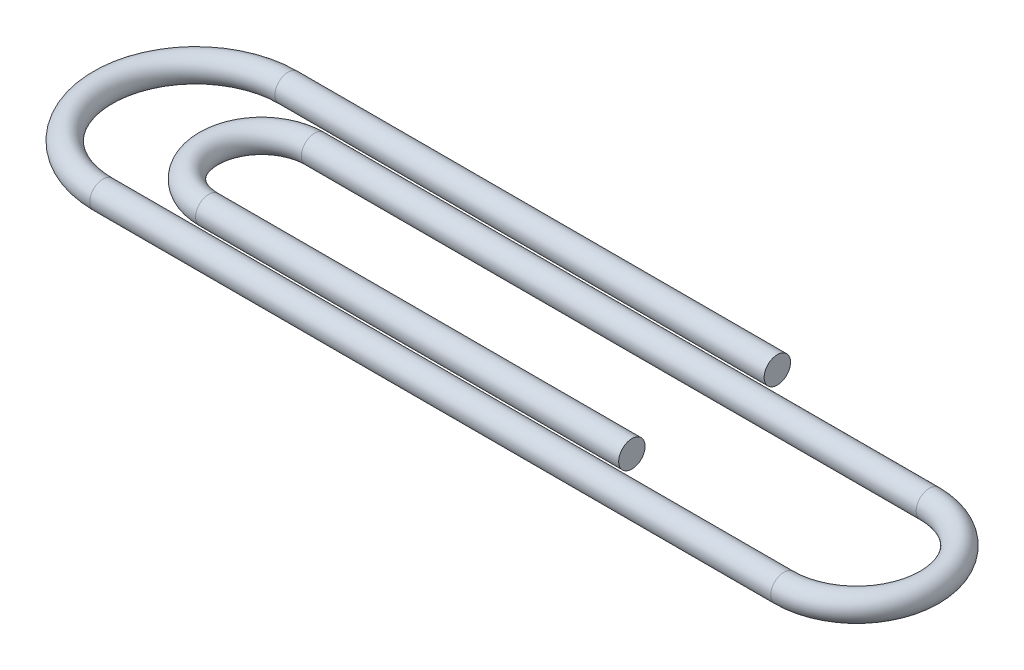
SolidWorks part; units mm, degrees
ref_plane "Front Plane" through (0, 0, 0) normal (0, 0, 1) x (1, 0, 0)
ref_plane "Top Plane" through (0, 0, 0) normal (0, 1, 0) x (1, 0, 0)
ref_plane "Right Plane" through (0, 0, 0) normal (1, 0, 0) x (0, 0, -1)
sketch "Sketch1" plane through (0, 0, 0) normal (0, 1, 0) x (1, 0, 0)
  line L0 (0, 0) -> (-16, 0)
  line L1 (-16, 0) -> (-16, 4) construction
  line L2 (-16, 4) -> (7.25, 4)
  line L3 (7.25, 4) -> (7.25, -1.5) construction
  line L4 (7.25, -1.5) -> (-18.5, -1.5)
  line L5 (-18.5, -1.5) -> (-18.5, 5.5) construction
  line L6 (-18.5, 5.5) -> (0, 5.5)
  arc A0 (-18.5, 5.5) -> (-18.5, -1.5) centre (-18.5, 2) ccw
  arc A1 (7.25, 4) -> (7.25, -1.5) centre (7.25, 1.25) cw
  arc A2 (-16, 4) -> (-16, 0) centre (-16, 2) ccw
  point P11 (-22, 2)
  point P13 (10, 1.25)
  point P14 (-18, 2)
  point P15 (0, 0)
  dimension "D1" = 32
  dimension "D4" = 3.5
  dimension "D2" = 10
  dimension "D3" = 4
  dimension "D5" = 1.5
  dimension "D6" = 1.5
sketch "Sketch3" plane through (0, 0, 0) normal (1, 0, 0) x (0, 0, -1)
  circle A0 centre (0, 0) radius 0.5
  dimension "D1" = 1
sweep "Sweep1" add profiles "Sketch3" path "Sketch1"
